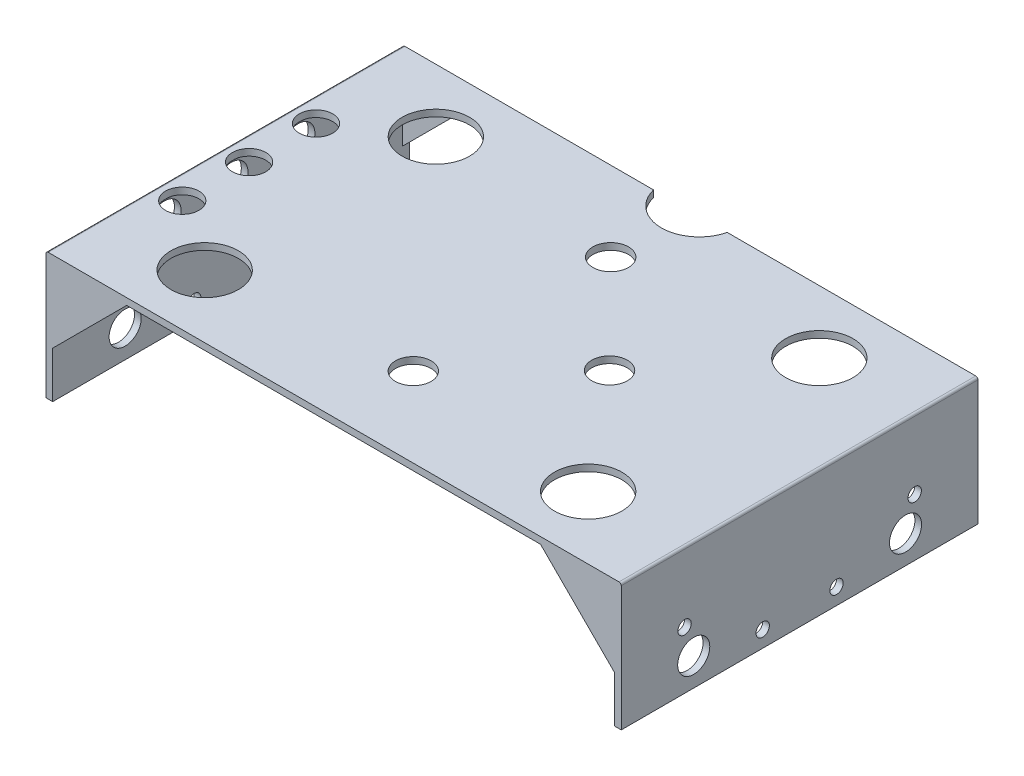
SolidWorks part; units mm, degrees
ref_plane "Front Plane" through (0, 0, 0) normal (0, 0, 1) x (1, 0, 0)
ref_plane "Top Plane" through (0, 0, 0) normal (0, 1, 0) x (1, 0, 0)
ref_plane "Right Plane" through (0, 0, 0) normal (1, 0, 0) x (0, 0, -1)
sketch "Croquis1" plane through (0, 0, 0) normal (0, 0, 1) x (1, 0, 0)
  line L0 (0, 0) -> (0, 28)
  line L1 (0.5, 28.5) -> (128.5, 28.5)
  line L2 (129, 28) -> (129, 0)
  line L3 (129, 0) -> (127.5, 0)
  line L4 (127.5, 0) -> (127.5, 26.5)
  line L5 (127, 27) -> (2, 27)
  line L6 (1.5, 26.5) -> (1.5, 0)
  line L7 (1.5, 0) -> (0, 0)
  arc A0 (127.5, 26.5) -> (127, 27) centre (127, 26.5) ccw
  arc A1 (2, 27) -> (1.5, 26.5) centre (2, 26.5) ccw
  arc A2 (128.5, 28.5) -> (129, 28) centre (128.5, 28) cw
  arc A3 (0, 28) -> (0.5, 28.5) centre (0.5, 28) cw
  point P4 (0, 0)
  point P10 (1.5, 4.9567)
  point P11 (1.5, 5.5399)
  point P12 (21.7806, 0)
  point P15 (127.5, 27)
  point P18 (1.5, 27)
  dimension "D4" = 0.5
  dimension "D1" = 1.5
  dimension "D2" = 1.5
  dimension "D3" = 1.5
  dimension "D5" = 128
  dimension "D6" = 28
extrude "Saliente-Extruir1" add sketch "Croquis1" along normal blind 80
sketch "Croquis2" plane through (0, 0, 0) normal (1, 0, 0) x (0, 0, -1)
  line L0 (-7.5, 0) -> (-7.5, 17.75) construction
  line L1 (-80, 0) -> (0, 0) construction
  line L2 (-7.5, 17.75) -> (-72.5, 17.75) construction
  line L3 (-72.5, 17.75) -> (-72.5, 0) construction
  point P4 (-40, 17.75)
  point P7 (-40, 0)
  dimension "D1" = 17.75
  dimension "D2" = 65
sketch "Croquis3" plane through (0, 0, 0) normal (1, 0, 0) x (0, 0, -1)
  line L0 (-40, 0) -> (-40, 28) construction
  line L1 (-80, 0) -> (0, 0) construction
  line L2 (-80, 28) -> (0, 28) construction
  line L3 (-72.5, 17.75) -> (-72.5, 0) construction
  circle A0 centre (-48.28, 3.65) radius 1.5
  circle A1 centre (-65.8, 12.85) radius 1.5
  circle A2 centre (-63.75, 6.26) radius 3.6
  circle A3 centre (-31.72, 3.65) radius 1.5
  circle A4 centre (-16.25, 6.26) radius 3.6
  circle A5 centre (-14.2, 12.85) radius 1.5
  dimension "D1" = 7.2
  dimension "D2" = 3
  dimension "D3" = 3
  dimension "D4" = 24.22
  dimension "D5" = 3.65
  dimension "D6" = 8.75
  dimension "D7" = 6.26
  dimension "D8" = 4.9
  dimension "D9" = 6.7
extrude "Cortar-Extruir2" cut sketch "Croquis3" along normal through all
sketch "Croquis4" plane through (0, 0, 0) normal (1, 0, 0) x (0, 0, -1)
  line L0 (-21.2, 22.7) -> (-58.7, 22.7) construction
  line L1 (-80, 28) -> (0, 28) construction
  line L2 (-80, 28) -> (-80, 0) construction
  circle A0 centre (-39.95, 22.7) radius 3.75
  circle A1 centre (-24.95, 22.7) radius 3.75
  circle A2 centre (-54.95, 22.7) radius 3.75
  point P6 (-59.3987, 22.5172)
  point P9 (0, 0)
  point P10 (-33.8809, 22.9078)
  point P11 (0, 0)
  point P12 (-47.2885, 25.2513)
  dimension "D1" = 7.5
  dimension "D2" = 37.5
  dimension "D3" = 5.3
  dimension "D4" = 21.3
extrude "Cortar-Extruir3" cut sketch "Croquis4" along normal blind 80
sketch "Croquis5" plane through (0, 0, 0) normal (0, 1, 0) x (1, 0, 0)
  line L0 (128.5, -40) -> (0, -40) construction
  line L1 (128.5, -80) -> (128.5, 0) construction
  line L2 (0, -7.5) -> (0, -72.5) construction
  line L3 (64.5, 0) -> (64.5, -80) construction
  line L4 (128.5, 0) -> (0.5, 0) construction
  line L5 (128.5, -80) -> (0.5, -80) construction
  line L6 (5.5, -58.7) -> (5.5, -21.2) construction
  line L8 (0.5, -80) -> (0.5, 0) construction
  circle A0 centre (64.25, -40) radius 27.25 construction
  circle A1 centre (64.25, -40) radius 17 construction
  circle A2 centre (21.5, -65.92) radius 7.565
  circle A4 centre (64.5, 2) radius 8.5
  circle A5 centre (86.38, -40) radius 4
  circle A6 centre (64.5, -17.87) radius 4
  circle A7 centre (64.5, -62.13) radius 4
  circle A8 centre (107.5, -65.92) radius 7.565
  circle A9 centre (21.5, -14.08) radius 7.565
  circle A10 centre (107.5, -14.08) radius 7.565
  circle A11 centre (5.5, -24.95) radius 3.75
  circle A12 centre (5.5, -39.95) radius 3.75
  circle A13 centre (5.5, -54.95) radius 3.75
  point P37 (0, 0)
  point P40 (0, 0)
  point P41 (0, 0)
  point P44 (0, 0)
  point P45 (0, 0)
  point P47 (0, 0)
  point P49 (0, 0)
  dimension "D1" = 54.5
  dimension "D2" = 34
  dimension "D3" = 8
  dimension "D4" = 8
  dimension "D5" = 8
  dimension "D9" = 17
  dimension "D11" = 15.13
  dimension "D6" = 22.13
  dimension "D7" = 22.13
  dimension "D8" = 22.13
  dimension "D10" = 2
  dimension "D12" = 14.08
  dimension "D13" = 43
  dimension "D14" = 5
extrude "Cortar-Extruir4" cut sketch "Croquis5" along normal blind 80
sketch "Croquis6" plane through (0, 0, 0) normal (0, 0, 1) x (1, 0, 0)
  line L0 (18.1043, 27) -> (1.5, 10.3957)
  line L1 (2, 27) -> (56.2386, 27) construction
  line L3 (1.5, 0) -> (1.5, 26.5) construction
  line L4 (18.1043, 27) -> (1.5, 27)
  line L5 (1.5, 27) -> (1.5, 10.3957)
  line L6 (64.5, 27) -> (64.5, 0) construction
  line L7 (56.2386, 27) -> (72.7614, 27) construction
  line L8 (127.5, 27) -> (127.5, 10.3957)
  line L9 (110.8957, 27) -> (127.5, 27)
  line L10 (110.8957, 27) -> (127.5, 10.3957)
  dimension "D1" = 45
  dimension "D2" = 16.6043
  dimension "D3" = 16.6043
extrude "Saliente-Extruir2" add sketch "Croquis6" along normal blind 1.5
ref_plane "Plano1" through (0, 0, 80) normal (0, 0, 1) x (1, 0, 0)
sketch "Croquis7" plane through (0, 0, 80) normal (0, 0, 1) x (1, 0, 0)
  line L0 (1.5, 27) -> (18.1043, 27)
  line L1 (18.1043, 27) -> (1.5, 10.3957)
  line L2 (1.5, 10.3957) -> (1.5, 27)
  line L3 (127.5, 27) -> (127.5, 10.3957)
  line L4 (127.5, 10.3957) -> (110.8957, 27)
  line L5 (110.8957, 27) -> (127.5, 27)
  point P10 (0, 0)
  point P13 (127.5, 27)
extrude "Saliente-Extruir4" add sketch "Croquis7" against normal blind 1.5
